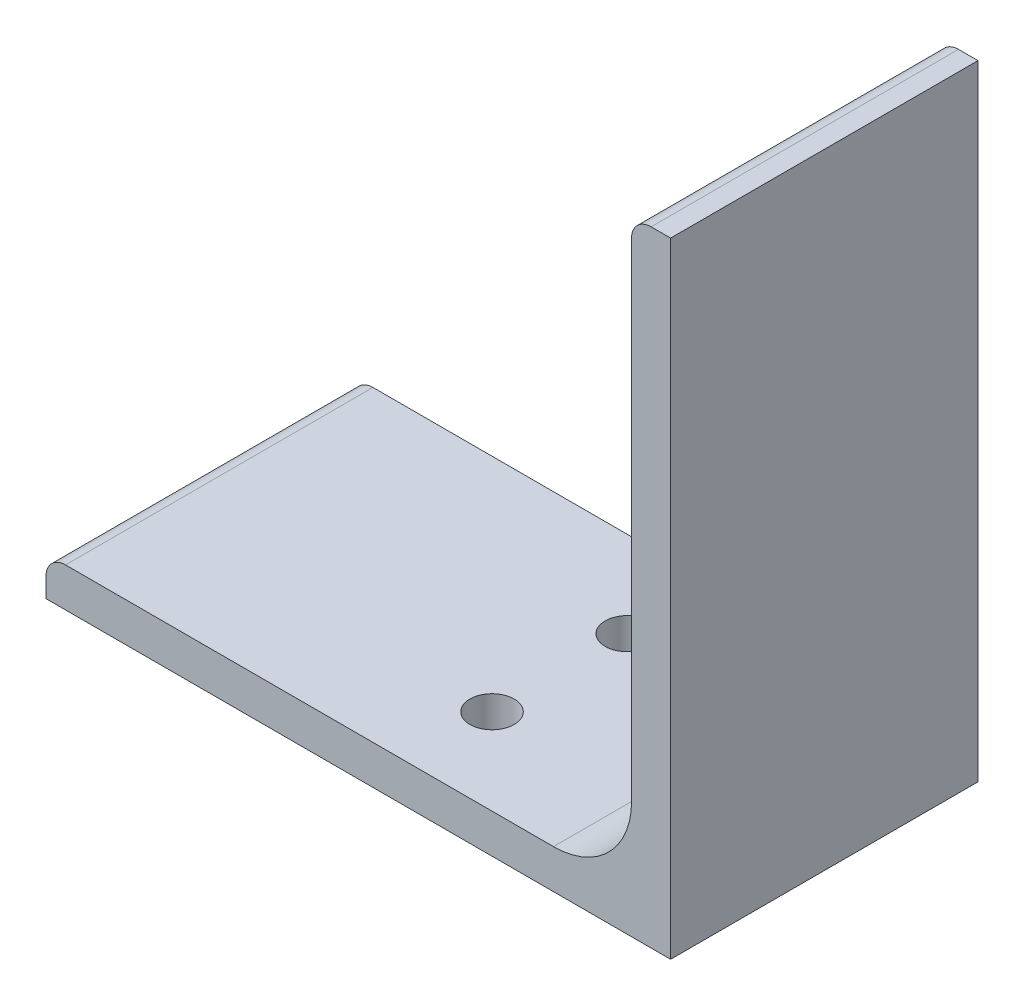
SolidWorks part; units mm, degrees
ref_plane "Front Plane" through (0, 0, 0) normal (0, 0, 1) x (1, 0, 0)
ref_plane "Top Plane" through (0, 0, 0) normal (0, 1, 0) x (1, 0, 0)
ref_plane "Right Plane" through (0, 0, 0) normal (1, 0, 0) x (0, 0, -1)
sketch "Sketch0" plane through (0, 0, 0) normal (0, 0, 1) x (1, 0, 0)
  line L0 (-25.4, -25.4) -> (25.4, -25.4)
  line L1 (25.4, -25.4) -> (25.4, 25.4)
  line L2 (25.4, 0) -> (0, 0) construction
  line L3 (0, 0) -> (0, -25.4) construction
  line L4 (22.225, -15.875) -> (22.225, 25.4) construction
  line L5 (15.875, -22.225) -> (-25.4, -22.225) construction
  arc A0 (22.225, -15.875) -> (15.875, -22.225) centre (15.875, -15.875) cw
  point P3 (20.3651, -20.3651)
  dimension "Inside Corner Radius" = 6.35
  dimension "Outside Height" = 50.8
  dimension "Inside Height" = 47.625
  dimension "Inside Width" = 47.625
  dimension "Wall Thickness" = 3.175
  dimension "D1" = 3.175
  dimension "Outside Width" = 50.8
sketch "Sketch1" plane through (0, 0, 0) normal (1, 0, 0) x (0, 0, -1)
  line L0 (12.5, 0) -> (-12.5, 0)
  point P4 (0, 0)
  dimension "Length" = 25
sketch "Sketch2" plane through (0, 0, 0) normal (0, 0, 1) x (1, 0, 0)
  line L0 (-25.4, -25.4) -> (25.4, -25.4)
  line L1 (25.4, -25.4) -> (25.4, 25.4)
  line L2 (25.4, 25.4) -> (22.225, 25.4) construction
  line L3 (22.225, 23.8125) -> (22.225, -15.875)
  line L4 (15.875, -22.225) -> (-23.8125, -22.225)
  line L5 (-25.4, -25.4) -> (-25.4, -22.225) construction
  line L6 (23.8125, 25.4) -> (25.4, 25.4)
  line L7 (-25.4, -23.8125) -> (-25.4, -25.4)
  line L8 (25.4, 0) -> (0, 0) construction
  line L9 (0, 0) -> (0, -25.4) construction
  arc A0 (22.225, 23.8125) -> (23.8125, 25.4) centre (23.8125, 23.8125) cw
  arc A1 (-25.4, -23.8125) -> (-23.8125, -22.225) centre (-23.8125, -23.8125) cw
  arc A2 (22.225, -15.875) -> (15.875, -22.225) centre (15.875, -15.875) cw
  dimension "Inside Radius" = 6.35
  dimension "Height" = 50.8
  dimension "Width" = 50.8
  dimension "Thickness" = 3.175
extrude "Boss-Extrude1" add sketch "Sketch2" along normal mid plane 25
sketch "Break Locations" plane through (0, 0, 0) normal (1, 0, 0) x (0, 0, -1)
  line L0 (39.316, 0) -> (-39.316, 0)
  line L1 (-12.5, -25.4) -> (-12.5, 25.4) construction
  line L2 (12.5, -25.4) -> (12.5, 25.4) construction
  point P0 (30.68, 0)
  point P1 (-30.68, 0)
  point P10 (0, 0)
  point P11 (-39.316, 0)
  point P13 (39.316, 0)
  dimension "D1" = 43.18
  dimension "D2" = 43.18
  dimension "D3" = 51.816
hole_wizard "M3 Clearance Hole1" positions "Sketch3" profile "Sketch4" hole size "M3" standard "ANSI Metric" end condition through all
sketch "Sketch3" plane through (0, -22.225, 0) normal (0, 1, 0) x (1, 0, 0)
  line L0 (15.875, -12.5) -> (15.875, 12.5) construction
  line L1 (15.875, -12.5) -> (-23.8125, -12.5) construction
  line L2 (15.875, 12.5) -> (-23.8125, 12.5) construction
  point P0 (3.875, 5.5)
  point P2 (3.875, -5.5)
  point P11 (0, 0)
  dimension "D1" = 12
  dimension "D2" = 7
  dimension "D3" = 7
sketch "Sketch4" plane through (3.875, -22.225, -5.5) normal (1, 0, 0) x (0, 0, 1)
  line L0 (0, 0) -> (0, 3.175)
  line L1 (0, 3.175) -> (1.8, 3.175)
  line L2 (1.8, 3.175) -> (1.8, 0)
  line L5 (1.8, 0) -> (0, 0)
  line L11 (0, -6.35) -> (0, 107.95) construction
  dimension "Thru Hole Dia." = 3.6
  dimension "Thru Hole Depth" = 3.175
equation "\"D1@Break Locations\" = .85 * \"Height@Sketch2\""
equation "\"D2@Break Locations\"=\"D1@Break Locations\""
equation "\"Thickness@Sketch2\"=\"wall thickness@sketch0\""
equation "\"Height@Sketch2\"=\"outside height@sketch0\""
equation "\"Width@Sketch2\"=\"outside width@sketch0\""
equation "\"Inside Radius@Sketch2\"=\"inside corner radius@sketch0\""
equation "\"Length@Boss-Extrude1\"=\"length@sketch1\""
equation "\"D3@Break Locations\"=\"D2@Break Locations\"*1.2"
equation "\"D1@Sketch0\"=\"Wall Thickness@Sketch0\""
equation "\"Length@Sketch1\"=25mm"
equation "\"D1@Sketch3\"=12mm"
equation "\"D2@Sketch3\"=7mm"
equation "\"D3@Sketch3\"=7mm"
